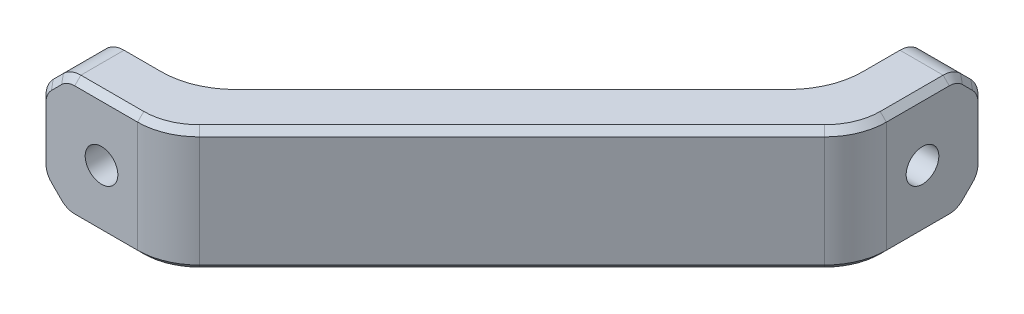
SolidWorks part; units mm, degrees
ref_plane "Front Plane" through (0, 0, 0) normal (0, 0, 1) x (1, 0, 0)
ref_plane "Top Plane" through (0, 0, 0) normal (0, 1, 0) x (1, 0, 0)
ref_plane "Right Plane" through (0, 0, 0) normal (1, 0, 0) x (0, 0, -1)
sketch "Sketch1" plane through (0, 0, 0) normal (0, 1, 0) x (1, 0, 0)
  line L0 (-4.1421, 0) -> (-20, 0)
  line L2 (56.5685, 60.7107) -> (56.5685, 76.5685)
  line L7 (53.6396, 53.6396) -> (2.9289, 2.9289)
  line L12 (-20, 0) -> (-20, 10)
  line L13 (56.5685, 76.5685) -> (46.5685, 76.5685)
  line L14 (46.5685, 76.5685) -> (46.5685, 64.8528)
  line L15 (43.6396, 57.7817) -> (-1.2132, 12.9289)
  line L16 (-8.2843, 10) -> (-20, 10)
  arc A2 (-4.1421, 0) -> (2.9289, 2.9289) centre (-4.1421, 10) ccw
  arc A3 (53.6396, 53.6396) -> (56.5685, 60.7107) centre (46.5685, 60.7107) ccw
  arc A4 (-1.2132, 12.9289) -> (-8.2843, 10) centre (-8.2843, 20) cw
  arc A5 (46.5685, 64.8528) -> (43.6396, 57.7817) centre (36.5685, 64.8528) cw
  point P4 (0, 0)
  point P8 (0, 0)
  point P11 (31.8198, 24.7487)
  point P12 (56.5685, 56.5685)
  dimension "D2" = 10
  dimension "D7" = 10
  dimension "D1" = 20
  dimension "D3" = 20
  dimension "D4" = 80
  dimension "D5" = 10
  dimension "D6" = 10
  dimension "5.00" = 10
extrude "Boss-Extrude1" add sketch "Sketch1" along normal blind 20
sketch "Sketch2" plane through (0, 0, 0) normal (0, 0, 1) x (1, 0, 0)
  circle A0 centre (-10, 10) radius 2.65
  dimension "D1" = 5.3
extrude "Cut-Extrude1" cut sketch "Sketch2" against normal blind 20
sketch "Sketch3" plane through (56.5685, 0, 0) normal (1, 0, 0) x (0, 0, -1)
  circle A0 centre (66.5685, 10) radius 2.65
  dimension "D1" = 5.3
extrude "Cut-Extrude2" cut sketch "Sketch3" against normal blind 20
sketch "Sketch7" plane through (46.5685, 0, 0) normal (-1, 0, 0) x (0, 0, 1)
  circle A0 centre (-66.5685, 10) radius 6
  dimension "D1" = 12
extrude "Cut-Extrude4" cut sketch "Sketch7" along normal blind 5
sketch "Sketch8" plane through (0, 0, -10) normal (0, 0, -1) x (-1, 0, 0)
  circle A0 centre (10, 10) radius 6
  dimension "D1" = 12
extrude "Cut-Extrude5" cut sketch "Sketch8" along normal blind 5
chamfer "Chamfer3" distance 4 angle 45 4 edges at (51.5685, 20, -76.5685) (51.5685, 0, -76.5685) (-20, 0, -5) (-20, 20, -5)
fillet "Fillet2" radius 4 8 edges at (51.5685, 4, -76.5685) (51.5685, 0, -72.5685) (51.5685, 20, -72.5685) (51.5685, 16, -76.5685) (-16, 20, -5) (-20, 16, -5) (-16, 0, -5) (-20, 4, -5)
chamfer "Chamfer4" distance 2 angle 45 24 edges at (21.2132, 20, -35.3553) (45.8073, 20, -61.026) (-4.4574, 20, -10.7612) (46.5685, 20, -67.8823) (-11.3137, 20, -10) (46.5685, 19.6955, -72.4424) (-15.8739, 19.6955, -10) (46.5685, 18, -74.5685) (-18, 18, -10) (46.5685, 15.8739, -76.2641) (-19.6955, 15.8739, -10) (46.5685, 10, -76.5685) (-20, 10, -10) (46.5685, 4.1261, -76.2641) (-19.6955, 4.1261, -10) (46.5685, 2, -74.5685) (-18, 2, -10) (46.5685, 0.3045, -72.4424) (-15.8739, 0.3045, -10) (46.5685, 0, -67.8823) (-11.3137, 0, -10) (45.8073, 0, -61.026) (-4.4574, 0, -10.7612) (21.2132, 0, -35.3553)
chamfer "Chamfer5" distance 1 angle 45 24 edges at (28.2843, 0, -28.2843) (-0.3153, 0, -0.7612) (55.8073, 0, -56.8838) (-9.2426, 0, 0) (56.5685, 0, -65.8112) (-15.8739, 0.3045, 0) (56.5685, 0.3045, -72.4424) (-18, 2, 0) (56.5685, 2, -74.5685) (-19.6955, 4.1261, 0) (56.5685, 4.1261, -76.2641) (-20, 10, 0) (56.5685, 10, -76.5685) (-19.6955, 15.8739, 0) (56.5685, 15.8739, -76.2641) (-18, 18, 0) (56.5685, 18, -74.5685) (-15.8739, 19.6955, 0) (56.5685, 19.6955, -72.4424) (-9.2426, 20, 0) (56.5685, 20, -65.8112) (-0.3153, 20, -0.7612) (55.8073, 20, -56.8838) (28.2843, 20, -28.2843)
